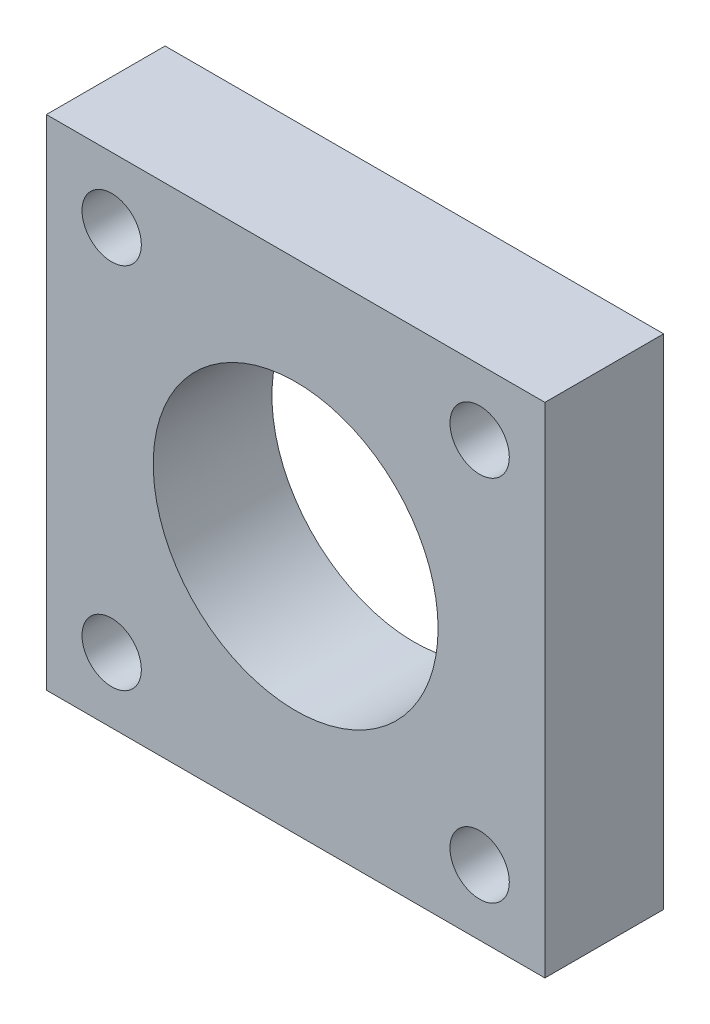
SolidWorks part; units mm, degrees
material "3.3547 (EN-AW 5083)"
ref_plane "Ebene vorne" through (0, 0, 0) normal (0, 0, 1) x (1, 0, 0)
ref_plane "Ebene oben" through (0, 0, 0) normal (0, 1, 0) x (1, 0, 0)
ref_plane "Ebene rechts" through (0, 0, 0) normal (1, 0, 0) x (0, 0, -1)
sketch "Skizze1" plane through (0, 0, 0) normal (0, 0, 1) x (1, 0, 0)
  line L1 (-28.3013, 16.3258) -> (13.6987, 16.3258)
  line L2 (-28.3013, 16.3258) -> (-28.3013, -25.6742)
  line L3 (-28.3013, -25.6742) -> (13.6987, -25.6742)
  line L4 (13.6987, 16.3258) -> (13.6987, -25.6742)
  line L5 (8.1987, -20.1742) -> (-22.8013, -20.1742) construction
  line L6 (8.1987, -20.1742) -> (8.1987, 10.8258) construction
  line L7 (8.1987, 10.8258) -> (-22.8013, 10.8258) construction
  line L8 (-22.8013, -20.1742) -> (-22.8013, 10.8258) construction
  line L9 (-7.3013, 10.8258) -> (-7.3013, -20.1742) construction
  line L10 (8.1987, -4.6742) -> (-22.8013, -4.6742) construction
  line L17 (8.1987, -51.1742) -> (8.1987, -20.1742) construction
  line L18 (8.1987, -20.1742) -> (-22.8013, -20.1742) construction
  circle A0 centre (-7.3013, -4.6742) radius 12
  circle A9 centre (-22.8013, 10.8258) radius 2.5
  circle A10 centre (8.1987, 10.8258) radius 2.5
  circle A11 centre (-22.8013, -20.1742) radius 2.5
  circle A12 centre (8.1987, -20.1742) radius 2.5
  dimension "D3" = 31
  dimension "D1" = 42
  dimension "D2" = 42
  dimension "D4" = 31
  dimension "D6" = 21
  dimension "D10" = 31
extrude "Aufsatz-Linear austragen1" add sketch "Skizze1" along normal blind 10
sketch "Skizze2" plane through (-28.3013, 0, 0) normal (-1, 0, 0) x (0, 0, 1)
  line L0 (10, -25.6742) -> (0, -25.6742) construction
  line L1 (10, 16.3258) -> (0, 16.3258) construction
  circle A0 centre (4, 4.3258) radius 1
  circle A1 centre (4, -13.6742) radius 1
  dimension "D1" = 12
  dimension "D2" = 12
extrude "Schnitt-Linear austragen1" cut sketch "Skizze2" against normal blind 8
hole_wizard "M4 Gewindebohrung1" positions "3D-Skizze1" profile "Skizze3" tap size "M4" standard "DIN"
sketch3d "3D-Skizze1"
  line L0 (-20.3013, 4.3258, 4) -> (-28.3013, 4.3258, 4) construction
  line L1 (-20.3013, -13.6742, 4) -> (-28.3013, -13.6742, 4) construction
  point P0 (-28.3013, 4.3258, 4)
  point P4 (-28.3013, -13.6742, 4)
sketch "Skizze3" plane through (-28.3013, 4.3258, 4) normal (0, 1, 0) x (0, 0, 1)
  line L0 (0, 0) -> (0, 12.4914)
  line L1 (0, 12.4914) -> (1.65, 11.5)
  line L2 (1.65, 11.5) -> (1.65, 0.375)
  line L3 (1.65, 0.375) -> (2.025, 0)
  line L5 (2.025, 0) -> (0, 0)
  line L6 (-1.65, 0.375) -> (-2.025, 0) construction
  line L10 (0, 12.4914) -> (-1.65, 11.5) construction
  line L11 (0, -6.35) -> (0, 107.95) construction
  dimension "Bohrerdurchmesser" = 3.3
  dimension "Bohrungstiefe" = 11.5
  dimension "Senkdurchmesser (Oben)" = 4.05
  dimension "Senkwinkel (Oben)" = 90
  dimension "Spitzenwinkel" = 118
cosmetic thread "Bohrungsgewinde1" parameters "D1"=8, "D2"=4
cosmetic thread "Bohrungsgewinde2" parameters "D1"=8, "D2"=4
